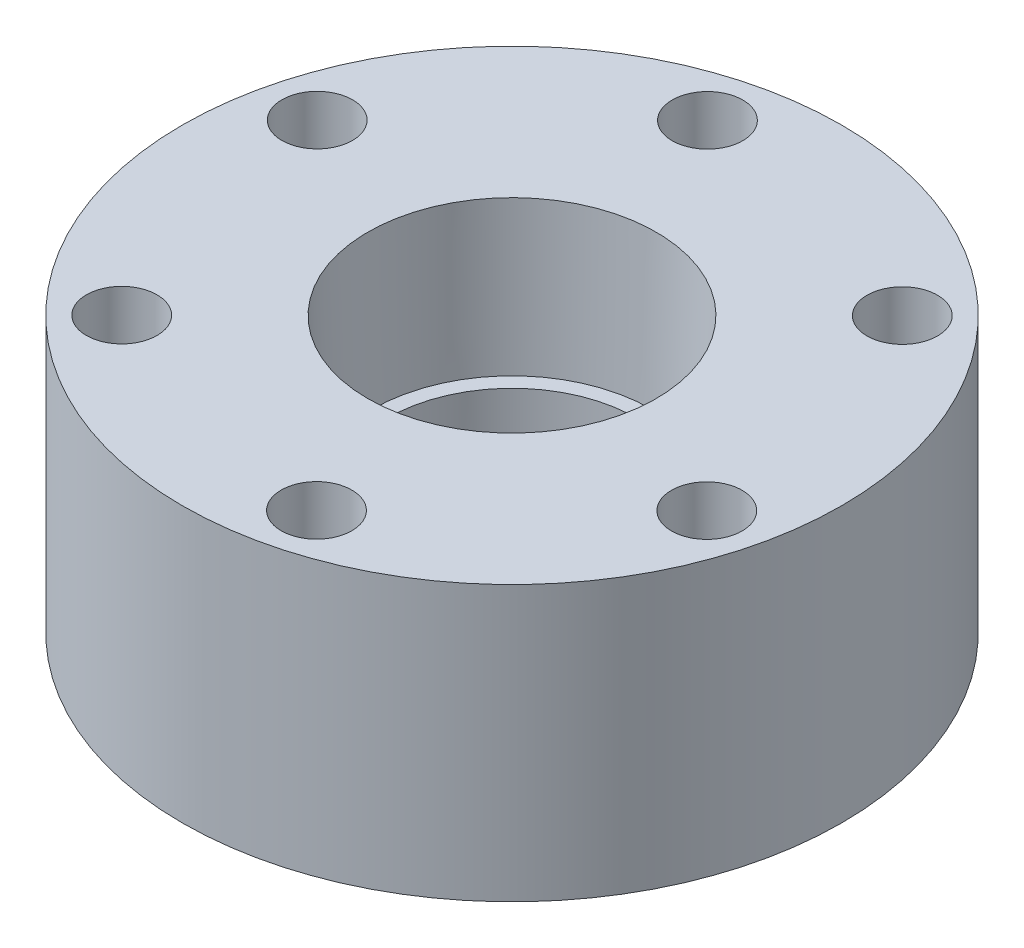
SolidWorks part; units mm, degrees
material "AISI 316 Stainless Steel Sheet (SS)"
ref_plane "Front Plane" through (0, 0, 0) normal (0, 0, 1) x (1, 0, 0)
ref_plane "Top Plane" through (0, 0, 0) normal (0, 1, 0) x (1, 0, 0)
ref_plane "Right Plane" through (0, 0, 0) normal (1, 0, 0) x (0, 0, -1)
sketch "Sketch1" plane through (0, 0, 0) normal (0, 1, 0) x (1, 0, 0)
  circle A0 centre (0, 0) radius 30.48
  dimension "D1" = 60.96
extrude "Boss-Extrude1" add sketch "Sketch1" along normal blind 25.4
sketch "Sketch2" plane through (0, 0, 0) normal (0, -1, 0) x (1, 0, 0)
  circle A0 centre (0, 0) radius 20.6502
  dimension "D1" = 41.3004
extrude "Cut-Extrude1" cut sketch "Sketch2" against normal blind 6.35
hole_wizard "3/4 NPT Tapped Hole1" positions "Sketch3" profile "Sketch4" size "3/4" standard "ANSI Inch" end condition through all
sketch "Sketch3" plane through (0, 25.4, 0) normal (0, 1, 0) x (1, 0, 0)
  point P0 (0, 0)
sketch "Sketch4" plane through (0, 25.4, 0) normal (1, 0, 0) x (0, 0, 1)
  line L0 (0, 0) -> (0, 25.4)
  line L1 (0, 25.4) -> (11.5062, 25.4)
  line L2 (-12.9142, 13.97) -> (-13.3325, 0) construction
  line L3 (11.5062, 25.4) -> (11.5062, 13.97)
  line L4 (11.5062, 13.97) -> (12.9142, 13.97)
  line L5 (12.9142, 13.97) -> (13.3325, 0)
  line L7 (13.3325, 0) -> (0, 0)
  line L8 (0, -6.35) -> (0, 107.95) construction
  line L11 (-11.5062, 13.97) -> (-12.9142, 13.97) construction
  dimension "Thru Tap Drill Dia." = 23.0124
  dimension "Thru Tap Drill Depth" = 25.4
  dimension "Thread Dia." = 26.665
  dimension "Thread Angle" = 3.43
  dimension "Thread Depth" = 13.97
hole_wizard "1/4 Clearance Hole1" positions "Sketch5" profile "Sketch6" hole size "1/4" standard "ANSI Inch" end condition through all
sketch "Sketch5" plane through (0, 25.4, 0) normal (0, 1, 0) x (1, 0, 0)
  point P0 (-24.6365, 6.6279)
  point P3 (-18.0582, -18.0219)
  point P6 (6.5783, -24.6498)
  point P12 (24.6365, -6.6279)
  point P15 (18.0582, 18.0219)
  point P18 (-6.5783, 24.6498)
sketch "Sketch6" plane through (-24.6365, 25.4, -6.6279) normal (1, 0, 0) x (0, 0, 1)
  line L0 (0, 0) -> (0, 25.4)
  line L1 (0, 25.4) -> (3.2639, 25.4)
  line L2 (3.2639, 25.4) -> (3.2639, 0)
  line L5 (3.2639, 0) -> (0, 0)
  line L11 (0, -6.35) -> (0, 107.95) construction
  dimension "Thru Hole Dia." = 6.5278
  dimension "Thru Hole Depth" = 25.4
